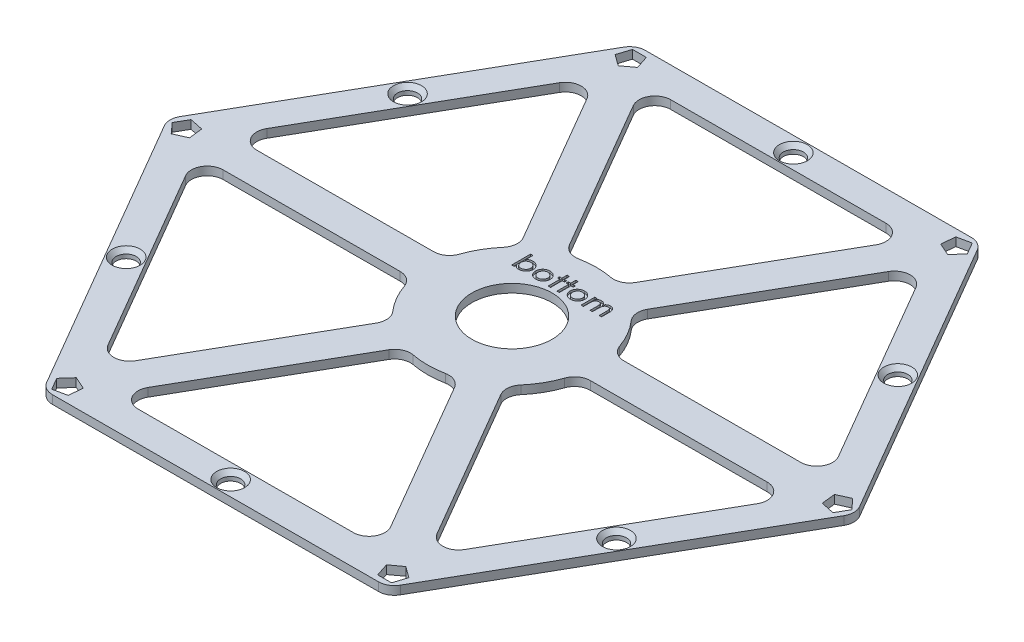
SolidWorks part; units mm, degrees
ref_plane "Front Plane" through (0, 0, 0) normal (0, 0, 1) x (1, 0, 0)
ref_plane "Top Plane" through (0, 0, 0) normal (0, 1, 0) x (1, 0, 0)
ref_plane "Right Plane" through (0, 0, 0) normal (1, 0, 0) x (0, 0, -1)
sketch "Sketch1" plane through (0, 0, 0) normal (0, 1, 0) x (1, 0, 0)
  line L0 (-31.0118, 53.34) -> (-30.9795, 42.6969) construction
  line L1 (-32.6705, 56.1929) -> (-64.9997, -0.197)
  line L2 (-64.9997, -0.197) -> (-32.3292, -56.3899)
  line L3 (-32.3292, -56.3899) -> (32.6705, -56.1929)
  line L4 (32.6705, -56.1929) -> (64.9997, 0.197)
  line L5 (64.9997, 0.197) -> (32.3292, 56.3899)
  line L6 (32.3292, 56.3899) -> (-32.6705, 56.1929)
  line L7 (-31.1934, 47.2773) -> (-56.5594, 3.0329)
  line L8 (-56.54, -3.3757) -> (-30.9063, -47.4655)
  line L9 (-25.3466, -50.6529) -> (25.6532, -50.4984)
  line L10 (31.1934, -47.2773) -> (56.5594, -3.0329)
  line L11 (56.54, 3.3757) -> (30.9063, 47.4655)
  line L12 (25.3466, 50.6529) -> (-25.6532, 50.4984)
  line L13 (-31.0118, 53.34) -> (-61.6997, -0.187) construction
  line L14 (-61.6997, -0.187) -> (-30.6879, -53.527) construction
  line L15 (-30.6879, -53.527) -> (31.0118, -53.34) construction
  line L16 (31.0118, -53.34) -> (61.6997, 0.187) construction
  line L17 (61.6997, 0.187) -> (30.6879, 53.527) construction
  line L18 (30.6879, 53.527) -> (-31.0118, 53.34) construction
  line L50 (28.7645, 52.4087) -> (31.1571, 51.3521)
  line L51 (-31.0051, 51.1151) -> (-28.8937, 52.6589)
  line L52 (-28.8937, 52.6589) -> (-29.7095, 55.144)
  line L58 (-31.1934, 47.2773) -> (-10.6492, 11.9413)
  line L60 (25.3466, 50.6529) -> (5.0169, 15.1931)
  line L66 (56.54, 3.3757) -> (15.6661, 3.2518)
  line L72 (31.1934, -47.2773) -> (10.6492, -11.9413)
  line L78 (-25.3466, -50.6529) -> (-5.0169, -15.1931)
  line L84 (-56.54, -3.3757) -> (-15.6661, -3.2518)
  line L89 (-5.1089, 15.1624) -> (-25.6532, 50.4984)
  line L91 (-29.7095, 55.144) -> (-32.325, 55.136)
  line L92 (10.5766, 12.0056) -> (30.9063, 47.4655)
  line L94 (-32.325, 55.136) -> (-33.1257, 52.6461)
  line L95 (15.6855, -3.1568) -> (56.5594, -3.0329)
  line L97 (-33.1257, 52.6461) -> (-31.0051, 51.1151)
  line L98 (5.1089, -15.1624) -> (25.6532, -50.4984)
  line L100 (31.1571, 51.3521) -> (32.9013, 53.3012)
  line L101 (-10.5766, -12.0056) -> (-30.9063, -47.4655)
  line L103 (32.9013, 53.3012) -> (31.5867, 55.5623)
  line L104 (-15.6855, 3.1568) -> (-56.5594, 3.0329)
  line L106 (31.5867, 55.5623) -> (29.03, 55.0108)
  line L107 (29.03, 55.0108) -> (28.7645, 52.4087)
  line L108 (59.7695, 1.2936) -> (60.0508, -1.3068)
  line L109 (60.0508, -1.3068) -> (62.6108, -1.8428)
  line L110 (62.6108, -1.8428) -> (63.9117, 0.4263)
  line L111 (63.9117, 0.4263) -> (62.1557, 2.3647)
  line L112 (62.1557, 2.3647) -> (59.7695, 1.2936)
  line L113 (31.0051, -51.1151) -> (28.8937, -52.6589)
  line L114 (28.8937, -52.6589) -> (29.7095, -55.144)
  line L115 (29.7095, -55.144) -> (32.325, -55.136)
  line L116 (32.325, -55.136) -> (33.1257, -52.6461)
  line L117 (33.1257, -52.6461) -> (31.0051, -51.1151)
  line L118 (-28.7645, -52.4087) -> (-31.1571, -51.3521)
  line L119 (-31.1571, -51.3521) -> (-32.9013, -53.3012)
  line L120 (-32.9013, -53.3012) -> (-31.5867, -55.5623)
  line L121 (-31.5867, -55.5623) -> (-29.03, -55.0108)
  line L122 (-29.03, -55.0108) -> (-28.7645, -52.4087)
  line L123 (-59.7695, -1.2936) -> (-60.0508, 1.3068)
  line L124 (-60.0508, 1.3068) -> (-62.6108, 1.8428)
  line L125 (-62.6108, 1.8428) -> (-63.9117, -0.4263)
  line L126 (-63.9117, -0.4263) -> (-62.1557, -2.3647)
  line L127 (-62.1557, -2.3647) -> (-59.7695, -1.2936)
  circle A0 centre (0, 0) radius 56.2917 construction
  circle A1 centre (0, 0) radius 50.5759 construction
  circle A2 centre (0, 0) radius 53.4338 construction
  circle A3 centre (-31.0118, 53.34) radius 1.8 construction
  arc A4 (-10.6492, 11.9413) -> (-15.6855, 3.1568) centre (0, 0) ccw
  arc A5 (5.0169, 15.1931) -> (-5.1089, 15.1624) centre (0, 0) ccw
  arc A6 (15.6661, 3.2518) -> (10.5766, 12.0056) centre (0, 0) ccw
  arc A7 (10.6492, -11.9413) -> (15.6855, -3.1568) centre (0, 0) ccw
  arc A8 (-5.0169, -15.1931) -> (5.1089, -15.1624) centre (0, 0) ccw
  arc A9 (-15.6661, -3.2518) -> (-10.5766, -12.0056) centre (0, 0) ccw
  circle A10 centre (-46.3558, 26.5765) radius 1.9
  circle A11 centre (-0.1619, 53.4335) radius 1.9
  circle A12 centre (46.1938, 26.857) radius 1.9
  circle A13 centre (46.3558, -26.5765) radius 1.9
  circle A14 centre (0.1619, -53.4335) radius 1.9
  circle A15 centre (-46.1938, -26.857) radius 1.9
  point P53 (0, 0)
  point P58 (-0.0078, -0.0152)
  point P70 (0, 0)
  point P87 (0, 0)
  dimension "D5" = 6
  dimension "D1" = 65
  dimension "D2" = 30
  dimension "D3" = 3.3
  dimension "D4" = 6
  dimension "D7" = 6
extrude "Boss-Extrude1" add sketch "Sketch1" along normal blind 1.6
fillet "Fillet1" radius 3 6 edges at (-64.9997, 0.8, 0.197) (-32.3292, 0.8, 56.3899) (32.6705, 0.8, 56.1929) (64.9997, 0.8, -0.197) (32.3292, 0.8, -56.3899) (-32.6705, 0.8, -56.1929)
sketch "Sketch2" plane through (0, 0, 0) normal (0, 1, 0) x (1, 0, 0)
fillet "Fillet2" radius 3 24 edges at (-25.3466, 0.8, 50.6529) (31.1934, 0.8, 47.2773) (25.6532, 0.8, 50.4984) (-30.9063, 0.8, 47.4655) (-56.54, 0.8, 3.3757) (-15.6661, 0.8, 3.2518) (-10.5766, 0.8, 12.0056) (-31.1934, 0.8, -47.2773) (-56.5594, 0.8, -3.0329) (-15.6855, 0.8, -3.1568) (-10.6492, 0.8, -11.9413) (-25.6532, 0.8, -50.4984) (25.3466, 0.8, -50.6529) (56.54, 0.8, -3.3757) (56.5594, 0.8, 3.0329) (30.9063, 0.8, -47.4655) (-5.0169, 0.8, 15.1931) (5.1089, 0.8, 15.1624) (10.6492, 0.8, 11.9413) (15.6855, 0.8, 3.1568) (15.6661, 0.8, -3.2518) (10.5766, 0.8, -12.0056) (5.0169, 0.8, -15.1931) (-5.1089, 0.8, -15.1624)
ref_plane "Plane1" through (0, 3.6, 0) normal (0, 1, 0) x (1, 0, 0)
sketch "Sketch3" plane through (0, 3.6, 0) normal (0, 1, 0) x (1, 0, 0)
  circle A0 centre (0, 0) radius 7.6
extrude "Cut-Extrude1" cut sketch "Sketch3" against normal blind 10
ref_plane "Plane2" through (0, 1.6, 0) normal (0, 1, 0) x (1, 0, 0)
sketch "Sketch4" plane through (0, 1.6, 0) normal (0, 1, 0) x (1, 0, 0)
  line L0 (-12.5635, 8.3459) -> (12.4774, 8.3459) construction
  text T0 "<b>bottom</b>\r\n"
extrude "Cut-Extrude2" cut sketch "Sketch4" against normal blind 0.4
chamfer "Chamfer1" distance 0.75 angle 48 6 edges at (0.1619, 1.6, 55.3335) (46.3558, 1.6, 28.4765) (46.1938, 1.6, -24.957) (-46.1938, 1.6, 28.757) (-46.3558, 1.6, -24.6765) (-0.1619, 1.6, -51.5335)
scale "Scale1" scale about centroid uniform scaling yes scale factor 1.15
